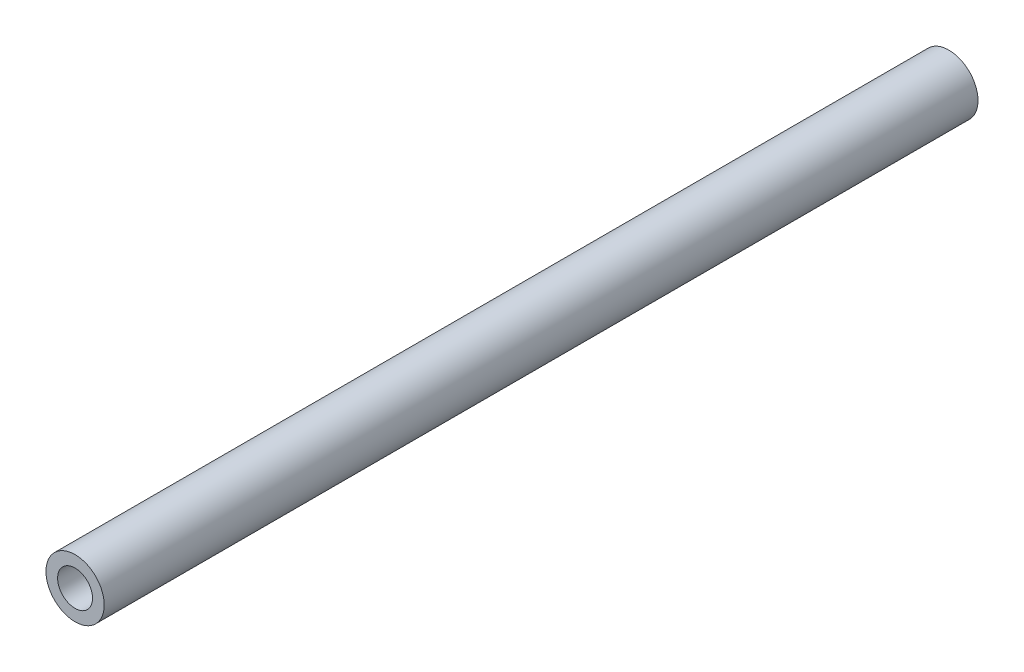
SolidWorks part; units mm, degrees
ref_plane "前视基准面" through (0, 0, 0) normal (0, 0, 1) x (1, 0, 0)
ref_plane "上视基准面" through (0, 0, 0) normal (0, 1, 0) x (1, 0, 0)
ref_plane "右视基准面" through (0, 0, 0) normal (1, 0, 0) x (0, 0, -1)
sketch "草图1" plane through (0, 0, 0) normal (0, 0, 1) x (1, 0, 0)
  circle A0 centre (0, 0) radius 2.5
  circle A1 centre (0, 0) radius 1.5
  dimension "D1" = 3
  dimension "D2" = 5
extrude "凸台-拉伸1" add sketch "草图1" along normal mid plane 75
